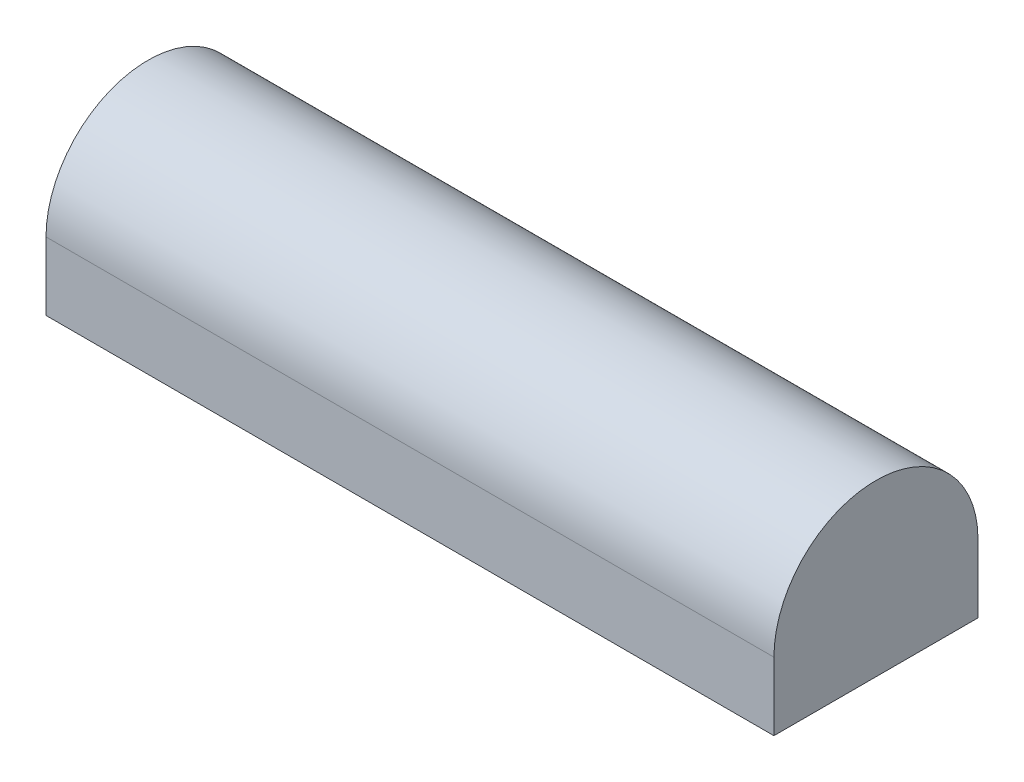
SolidWorks part; units mm, degrees
ref_plane "Front Plane" through (0, 0, 0) normal (0, 0, 1) x (1, 0, 0)
ref_plane "Top Plane" through (0, 0, 0) normal (0, 1, 0) x (1, 0, 0)
ref_plane "Right Plane" through (0, 0, 0) normal (1, 0, 0) x (0, 0, -1)
sketch "Sketch1" plane through (0, 0, 0) normal (1, 0, 0) x (0, 0, -1)
  line L0 (-1.5, 0) -> (-1.5, -1)
  line L1 (-1.5, -1) -> (1.5, -1)
  line L2 (1.5, -1) -> (1.5, 0)
  line L3 (-1.5, 0) -> (1.5, 0)
  arc A0 (-1.5, 0) -> (1.5, 0) centre (0, 0) cw
  dimension "D1" = 1
  dimension "D2" = 3
extrude "Boss-Extrude1" add sketch "Sketch1" along normal blind 10.7 contours A0 L3 | L3 L0 L1 L2
